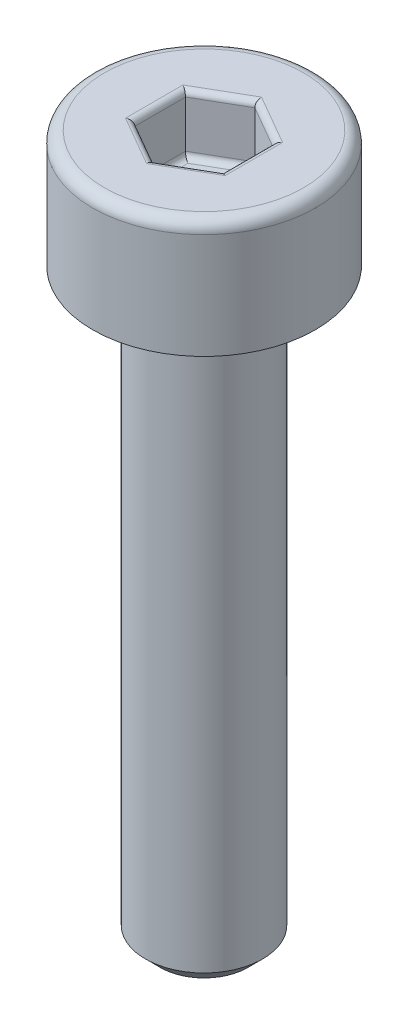
SolidWorks part; units mm, degrees
ref_plane "Front Plane" through (0, 0, 0) normal (0, 0, 1) x (1, 0, 0)
ref_plane "Top Plane" through (0, 0, 0) normal (0, 1, 0) x (1, 0, 0)
ref_plane "Right Plane" through (0, 0, 0) normal (1, 0, 0) x (0, 0, -1)
sketch "Sketch1" plane through (0, 0, 0) normal (0, 0, 1) x (1, 0, 0)
  line L0 (0, 0) -> (0, -47.0967) construction
  line L1 (0, -12) -> (-1, -12)
  line L2 (-1, -12) -> (-1, -2)
  line L3 (-1, -2) -> (-1.9, -2)
  line L4 (-1.9, -2) -> (-1.9, 0)
  line L5 (-1.9, 0) -> (0, 0)
  line L6 (0, 0) -> (0, -12)
  dimension "d" = 2
  dimension "l" = 12
  dimension "k" = 2
  dimension "dk" = 3.8
revolve "Revolve1" add sketch "Sketch1" angle 360 about L0
chamfer "Chamfer1" distance 0.25 angle 45 2 edges at (0, -2, 1) (0, -12, 1)
fillet "Fillet1" radius 0.2 1 edges at (0, 0, 1.9)
sketch "Sketch2" plane through (0, 0, 0) normal (0, 1, 0) x (1, 0, 0)
  line L1 (0, 0.866) -> (-0.75, 0.433)
  line L2 (-0.75, 0.433) -> (-0.75, -0.433)
  line L3 (-0.75, -0.433) -> (0, -0.866)
  line L4 (0, -0.866) -> (0.75, -0.433)
  line L5 (0.75, -0.433) -> (0.75, 0.433)
  line L6 (0.75, 0.433) -> (0, 0.866)
  circle A0 centre (0, 0) radius 0.75 construction
  dimension "s" = 1.5
extrude "Cut-Extrude1" cut sketch "Sketch2" against normal blind 1
fillet "Fillet2" radius 0.1 12 edges at (-0.375, 0, -0.6495) (-0.75, 0, 0) (-0.375, 0, 0.6495) (0.375, 0, 0.6495) (0.75, 0, 0) (0.375, 0, -0.6495) (0.75, -1, 0) (0.375, -1, 0.6495) (-0.375, -1, 0.6495) (-0.75, -1, 0) (-0.375, -1, -0.6495) (0.375, -1, -0.6495)
